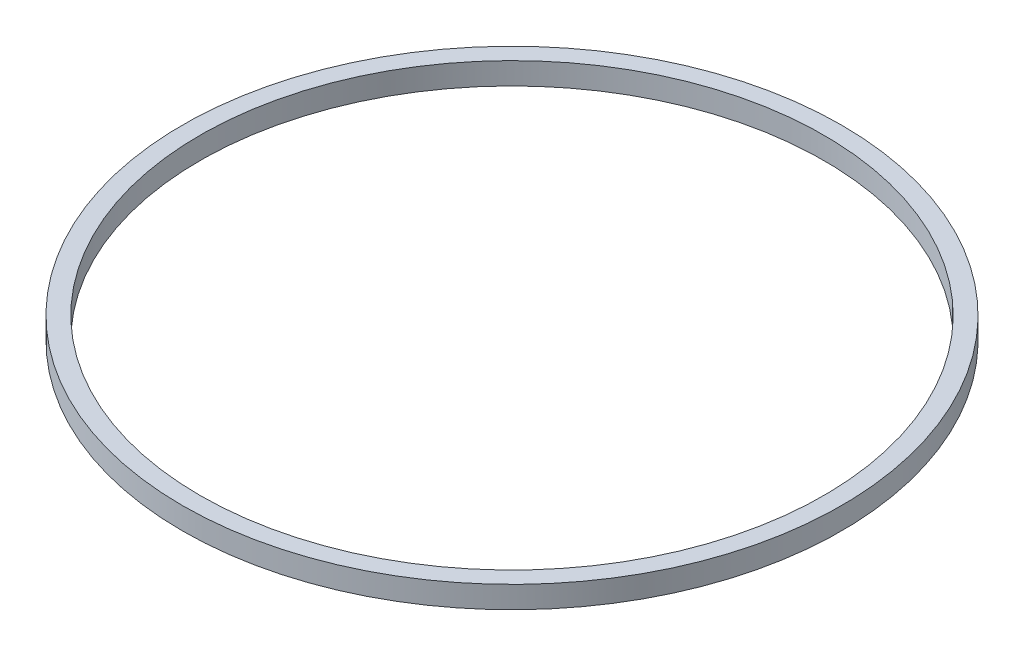
SolidWorks part; units mm, degrees
ref_plane "Front Plane" through (0, 0, 0) normal (0, 0, 1) x (1, 0, 0)
ref_plane "Top Plane" through (0, 0, 0) normal (0, 1, 0) x (1, 0, 0)
ref_plane "Right Plane" through (0, 0, 0) normal (1, 0, 0) x (0, 0, -1)
sketch "Sketch1" plane through (0, 0, 0) normal (0, 1, 0) x (1, 0, 0)
  circle A0 centre (0, 0) radius 75
  circle A1 centre (0, 0) radius 71
  dimension "D1" = 142
  dimension "D2" = 150
extrude "Boss-Extrude1" add sketch "Sketch1" along normal blind 5
